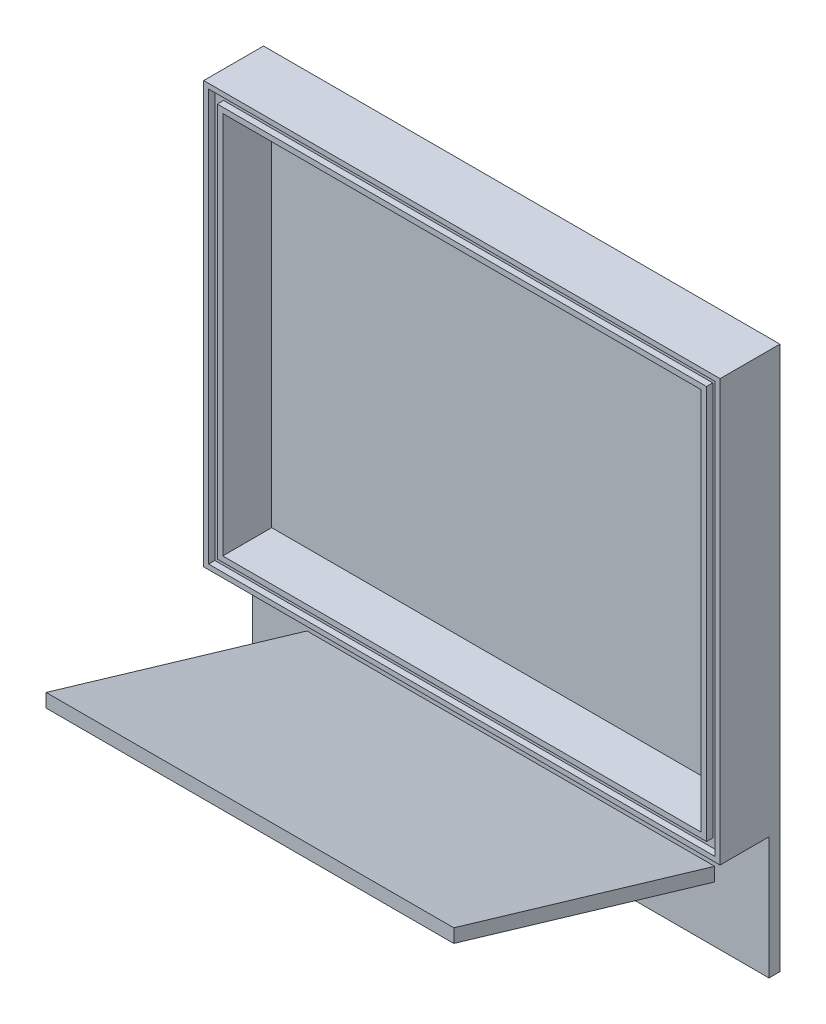
SolidWorks part; units mm, degrees
ref_plane "Front Plane" through (0, 0, 0) normal (0, 0, 1) x (1, 0, 0)
ref_plane "Top Plane" through (0, 0, 0) normal (0, 1, 0) x (1, 0, 0)
ref_plane "Right Plane" through (0, 0, 0) normal (1, 0, 0) x (0, 0, -1)
sketch "190 x 200 Tray Floor Sketch" plane through (0, 0, 0) normal (0, 0, 1) x (1, 0, 0)
  line L1 (-95, 0) -> (95, 0)
  line L2 (-95, 0) -> (-95, 200)
  line L3 (-95, 200) -> (95, 200)
  line L4 (95, 0) -> (95, 200)
extrude "4 mm Tray Floor" add sketch "190 x 200 Tray Floor Sketch" along normal blind 4 separate body
sketch "Electronics Compartment Wall Sketch" plane through (0, 0, 0) normal (0, 0, 1) x (1, 0, 0)
  line L0 (-95, 200) -> (-95, 0) construction
  line L1 (-95, 45) -> (95, 45)
  line L2 (-95, 45) -> (-95, 200)
  line L3 (-95, 200) -> (95, 200)
  line L4 (95, 45) -> (95, 200)
  line L6 (-88, 52) -> (88, 52)
  line L7 (-88, 52) -> (-88, 193)
  line L8 (-88, 193) -> (88, 193)
  line L9 (88, 52) -> (88, 193)
extrude "22 mm Perimeter Walls" add sketch "Electronics Compartment Wall Sketch" along normal blind 22
sketch "3 mm Cord Gasket Groove Sketch" plane through (0, 0, 0) normal (0, 0, 1) x (1, 0, 0)
  line L1 (-93.2, 46.8) -> (93.2, 46.8)
  line L2 (-93.2, 46.8) -> (-93.2, 198.2)
  line L3 (-93.2, 198.2) -> (93.2, 198.2)
  line L4 (93.2, 46.8) -> (93.2, 198.2)
  line L5 (-90, 50) -> (90, 50)
  line L6 (-90, 50) -> (-90, 195)
  line L7 (-90, 195) -> (90, 195)
  line L8 (90, 50) -> (90, 195)
extrude "3.2 x 2.3 mm Perimeter Gasket Groove" cut sketch "3 mm Cord Gasket Groove Sketch" against normal blind 2.3 from offset 22
sketch "Angled Display Bulkhead Side Profile" plane through (0, 0, 0) normal (1, 0, 0) x (0, 0, -1)
  line L0 (-2, 20) -> (-2, 25)
  line L1 (-2, 25) -> (-100, 54)
  line L2 (-100, 54) -> (-100, 49)
  line L3 (-100, 49) -> (-2, 20)
extrude "150 mm Wide Angled Display Bulkhead" add sketch "Angled Display Bulkhead Side Profile" along normal blind 75 and the other way blind 75
